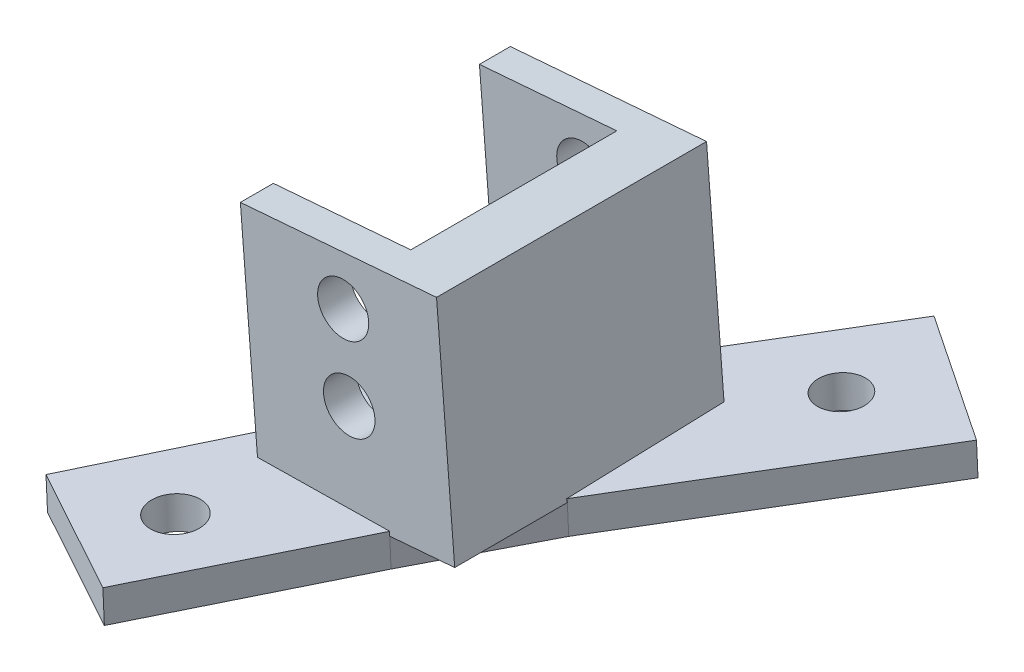
SolidWorks part; units mm, degrees
ref_plane "Front Plane" through (0, 0, 0) normal (0, 0, 1) x (1, 0, 0)
ref_plane "Top Plane" through (0, 0, 0) normal (0, 1, 0) x (1, 0, 0)
ref_plane "Right Plane" through (0, 0, 0) normal (1, 0, 0) x (0, 0, -1)
sketch "Sketch1" plane through (0, 0, 0) normal (0, 0, 1) x (1, 0, 0)
  line L0 (-199.0449, 238.7124) -> (-196.8076, 210.9895)
  line L1 (-210.3781, 237.7978) -> (-182.1129, 240.0788) construction
  line L2 (-196.8076, 210.9895) -> (-172.6304, 212.9406)
  line L3 (-172.6304, 212.9406) -> (-174.8677, 240.6635)
  line L4 (-174.8677, 240.6635) -> (-199.0449, 238.7124)
  line L5 (-184.9478, 216.0238) -> (-197.1346, 215.0403)
  line L6 (-216.6262, 213.4673) -> (-184.9478, 216.0238) construction
  arc A0 (-182.1129, 240.0788) -> (-179.0978, 231.1866) centre (-186.3724, 233.6772) cw
  arc A1 (-179.0978, 231.1866) -> (-178.8038, 227.2073) centre (-174.2916, 229.5411) ccw
  arc A2 (-178.8038, 227.2073) -> (-184.9478, 216.0238) centre (-185.6285, 223.6772) cw
  dimension "D1" = 5.842
  dimension "D2" = 4.064
extrude "Boss-Extrude1" add sketch "Sketch1" against normal blind 29.21 contours A1 A2 L5 L0 L2 L3 L4 A0
sketch "Sketch2" plane through (0, 0, 0) normal (0, 0, 1) x (1, 0, 0)
  line L0 (-174.8677, 240.6635) -> (-172.6304, 212.9406)
  line L1 (-172.6304, 212.9406) -> (-196.8076, 210.9895)
  line L2 (-174.8677, 240.6635) -> (-199.0449, 238.7124)
  line L3 (-210.3781, 237.7978) -> (-182.1129, 240.0788) construction
  line L4 (-199.0449, 238.7124) -> (-196.8076, 210.9895)
  circle A1 centre (-185.6285, 223.6772) radius 3.175
  circle A2 centre (-186.3724, 233.6772) radius 3.1509
extrude "Boss-Extrude2" add sketch "Sketch2" along normal blind 4.064
sketch "Sketch3" plane through (0, 0, -29.21) normal (0, 0, -1) x (-1, 0, 0)
  line L0 (197.1346, 215.0403) -> (199.0449, 238.7124)
  line L1 (199.0449, 238.7124) -> (182.1129, 240.0788)
  line L2 (184.9478, 216.0238) -> (197.1346, 215.0403)
  arc A0 (182.1129, 240.0788) -> (179.0978, 231.1866) centre (186.3724, 233.6772) ccw
  arc A1 (179.0978, 231.1866) -> (178.8038, 227.2073) centre (174.2916, 229.5411) cw
  arc A2 (178.8038, 227.2073) -> (184.9478, 216.0238) centre (185.6285, 223.6772) ccw
  circle A3 centre (186.3724, 233.6772) radius 3.1509
  circle A4 centre (185.6285, 223.6772) radius 3.175
extrude "Boss-Extrude3" add sketch "Sketch3" against normal up to surface (3.81 mm away)
ref_plane "Plane1" through (-3.4011, 215.5353, 6.5552) normal (-0.0158, 0.9994, 0.0304) x (0.9999, 0.0158, 0.0005)
sketch "Sketch4" plane through (-3.4011, 215.5353, 6.5552) normal (-0.0158, 0.9994, 0.0304) x (0.9999, 0.0158, 0.0005)
  line L0 (-178.9185, 35.9977) -> (-164.8286, 57.0876)
  line L1 (-164.8286, 57.0876) -> (-149.0448, 46.5426)
  line L2 (-149.0448, 46.5426) -> (-169.257, 16.289)
  line L3 (-169.2663, 35.6698) -> (-169.2504, 2.4112) construction
  line L4 (-177.2656, 2.3915) -> (-189.8022, -20.4215)
  line L5 (-193.4554, 2.3518) -> (-169.2504, 2.4112) construction
  line L6 (-189.8022, -20.4215) -> (-205.369, -11.8669)
  line L7 (-205.369, -11.8669) -> (-194.5391, 8.2798)
  line L8 (-213.4344, 8.2335) -> (-175.6438, 8.3261) construction
  line L9 (-169.257, 16.289) -> (-177.2656, 2.3915)
  line L10 (-178.9185, 35.9977) -> (-194.5391, 8.2798)
  circle A1 centre (-162.7888, 43.6305) radius 2.9121
  circle A2 centre (-192.8703, -8.4041) radius 3.0352
extrude "Boss-Extrude4" add sketch "Sketch4" against normal blind 4.064
